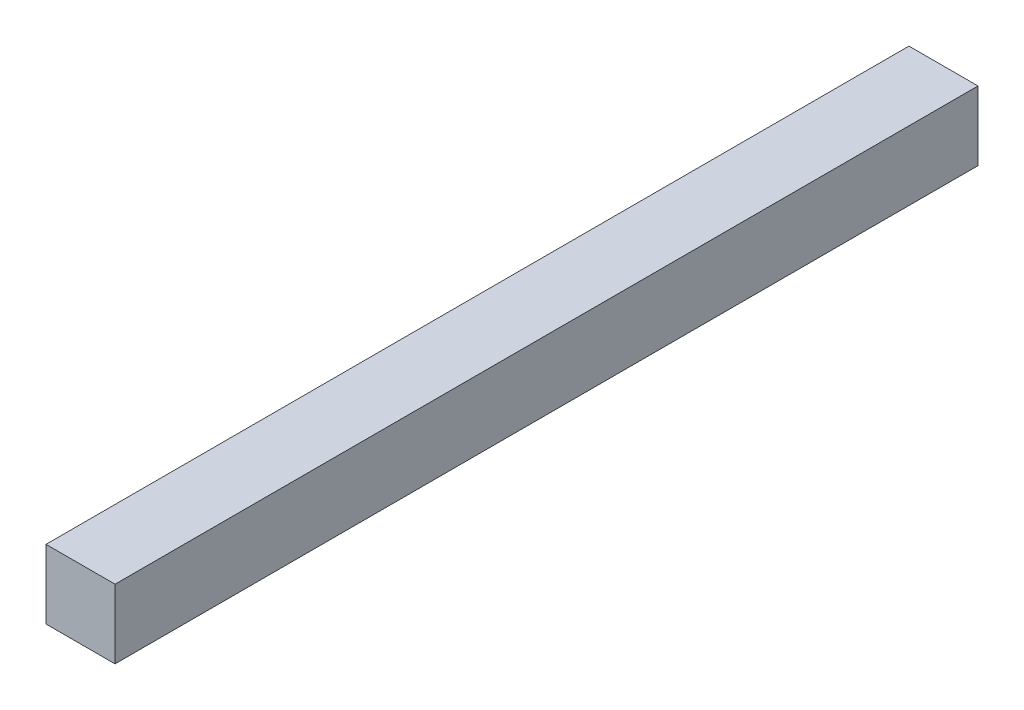
SolidWorks part; units mm, degrees
ref_plane "前视基准面" through (0, 0, 0) normal (0, 0, 1) x (1, 0, 0)
ref_plane "上视基准面" through (0, 0, 0) normal (0, 1, 0) x (1, 0, 0)
ref_plane "右视基准面" through (0, 0, 0) normal (1, 0, 0) x (0, 0, -1)
other "Configuration Table"
sketch "草图1" plane through (0, 0, 0) normal (0, 0, 1) x (1, 0, 0)
  line L1 (-10, 10) -> (10, 10)
  line L2 (-10, 10) -> (-10, -10)
  line L3 (-10, -10) -> (10, -10)
  line L4 (10, 10) -> (10, -10)
  line L5 (-10, 10) -> (10, -10) construction
  line L6 (-10, -10) -> (10, 10) construction
  point P0 (0, 0)
  point P6 (10, 0)
extrude "凸台-拉伸1" add sketch "草图1" along normal blind 250
